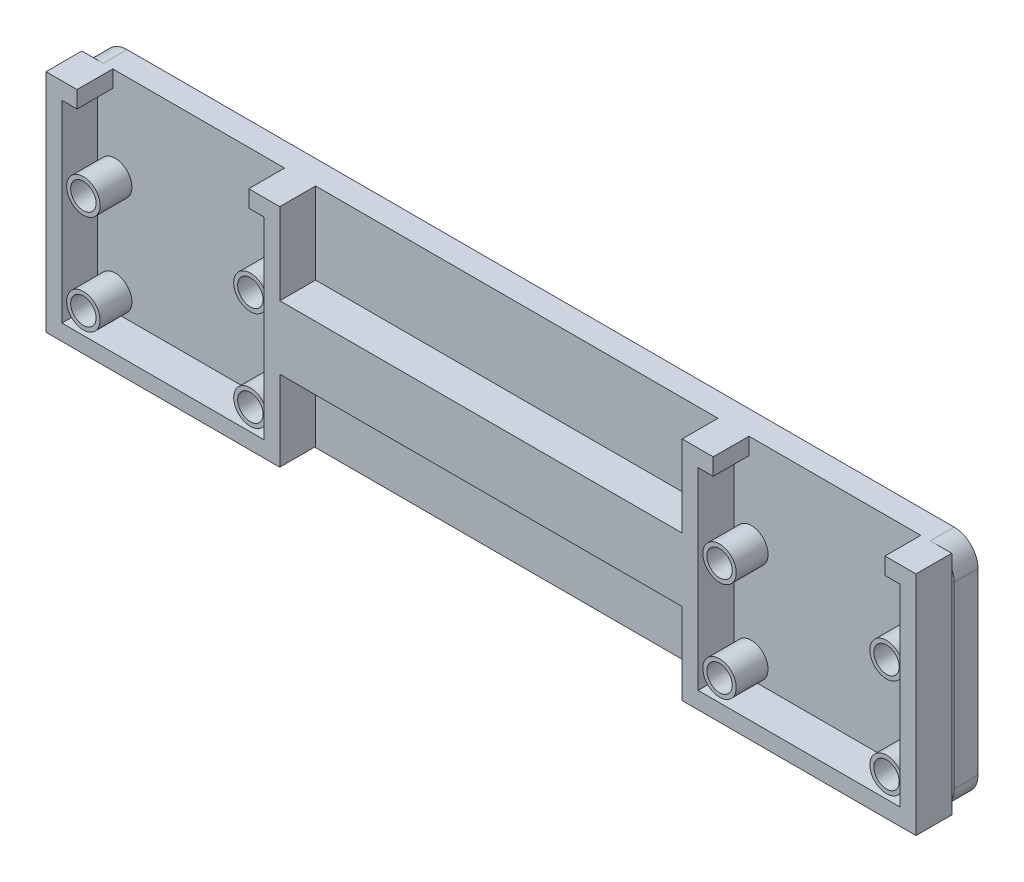
SolidWorks part; units mm, degrees
ref_plane "Front Plane" through (0, 0, 0) normal (0, 0, 1) x (1, 0, 0)
ref_plane "Top Plane" through (0, 0, 0) normal (0, 1, 0) x (1, 0, 0)
ref_plane "Right Plane" through (0, 0, 0) normal (1, 0, 0) x (0, 0, -1)
sketch "Sketch1" plane through (0, 0, 0) normal (0, 0, 1) x (1, 0, 0)
  line L1 (-55, -14.25) -> (55, -14.25)
  line L2 (-55, -14.25) -> (-55, 14.25)
  line L3 (-55, 14.25) -> (55, 14.25)
  line L4 (55, -14.25) -> (55, 14.25)
extrude "Backplate_Base" add sketch "Sketch1" along normal blind 3
fillet "Outer_Corner_Fillets" radius 3 4 edges at (-55, 14.25, 1.5) (55, 14.25, 1.5) (55, -14.25, 1.5) (-55, -14.25, 1.5)
sketch "Sketch2" plane through (0, 0, 3) normal (0, 0, 1) x (1, 0, 0)
  line L0 (52, 14.25) -> (-52, 14.25) construction
  line L1 (-54.7, -14.131) -> (-25.3, -14.131)
  line L2 (-54.7, -14.131) -> (-54.7, 14.25)
  line L3 (-54.7, 14.25) -> (-25.3, 14.25)
  line L4 (-25.3, -14.131) -> (-25.3, 14.25)
  line L5 (-52, -14.25) -> (52, -14.25) construction
  line L6 (-52.7, -12.131) -> (-27.3, -12.131)
  line L7 (-52.7, -12.131) -> (-52.7, 12.131)
  line L8 (-52.7, 12.131) -> (-27.3, 12.131)
  line L9 (-27.3, -12.131) -> (-27.3, 12.131)
  line L10 (25.3, -14.25) -> (54.7, -14.25)
  line L11 (25.3, -14.25) -> (25.3, 14.25)
  line L12 (25.3, 14.25) -> (54.7, 14.25)
  line L13 (54.7, -14.25) -> (54.7, 14.25)
  line L15 (27.3, -12.131) -> (52.7, -12.131)
  line L16 (27.3, -12.131) -> (27.3, 12.131)
  line L17 (27.3, 12.131) -> (52.7, 12.131)
  line L18 (52.7, -12.131) -> (52.7, 12.131)
extrude "Pocket_Walls" add sketch "Sketch2" along normal blind 4.5
sketch "Sketch3" plane through (0, 0, 3) normal (0, 0, 1) x (1, 0, 0)
  line L0 (-25.3, -14.131) -> (-25.3, 14.25) construction
  line L1 (-25.3, -4) -> (25.3, -4)
  line L2 (-25.3, -4) -> (-25.3, 4)
  line L3 (-25.3, 4) -> (25.3, 4)
  line L4 (25.3, -4) -> (25.3, 4)
  line L5 (25.3, 14.25) -> (25.3, -14.25) construction
extrude "Center_Bridge" add sketch "Sketch3" along normal blind 4.5
sketch "Sketch4" plane through (0, 0, 7.5) normal (0, 0, 1) x (1, 0, 0)
  line L1 (-50.8, 11.631) -> (-29.2, 11.631)
  line L2 (-50.8, 11.631) -> (-50.8, 14.631)
  line L3 (-50.8, 14.631) -> (-29.2, 14.631)
  line L4 (-29.2, 11.631) -> (-29.2, 14.631)
  line L5 (29.2, 11.631) -> (50.8, 11.631)
  line L6 (29.2, 11.631) -> (29.2, 14.631)
  line L7 (29.2, 14.631) -> (50.8, 14.631)
  line L8 (50.8, 11.631) -> (50.8, 14.631)
extrude "CSI_Cable_Exit_Slots" cut sketch "Sketch4" against normal blind 4.5
sketch "Sketch5" plane through (0, 0, 0) normal (0, 0, 1) x (1, 0, 0)
  circle A0 centre (-50.5, -9.931) radius 2.1
  circle A1 centre (-29.5, -9.931) radius 2.1
  circle A2 centre (-50.5, 2.569) radius 2.1
  circle A3 centre (-29.5, 2.569) radius 2.1
  circle A4 centre (29.5, -9.931) radius 2.1
  circle A5 centre (50.5, -9.931) radius 2.1
  circle A6 centre (29.5, 2.569) radius 2.1
  circle A7 centre (50.5, 2.569) radius 2.1
extrude "Standoff_Bosses" add sketch "Sketch5" along normal blind 4 from offset 3
sketch "Sketch6" plane through (0, 0, 7) normal (0, 0, 1) x (1, 0, 0)
  circle A0 centre (-50.5, -9.931) radius 1.6
  circle A1 centre (-29.5, -9.931) radius 1.6
  circle A2 centre (-50.5, 2.569) radius 1.6
  circle A3 centre (-29.5, 2.569) radius 1.6
  circle A4 centre (29.5, -9.931) radius 1.6
  circle A5 centre (50.5, -9.931) radius 1.6
  circle A6 centre (29.5, 2.569) radius 1.6
  circle A7 centre (50.5, 2.569) radius 1.6
extrude "M2_Insert_Holes" cut sketch "Sketch6" against normal blind 4.5
